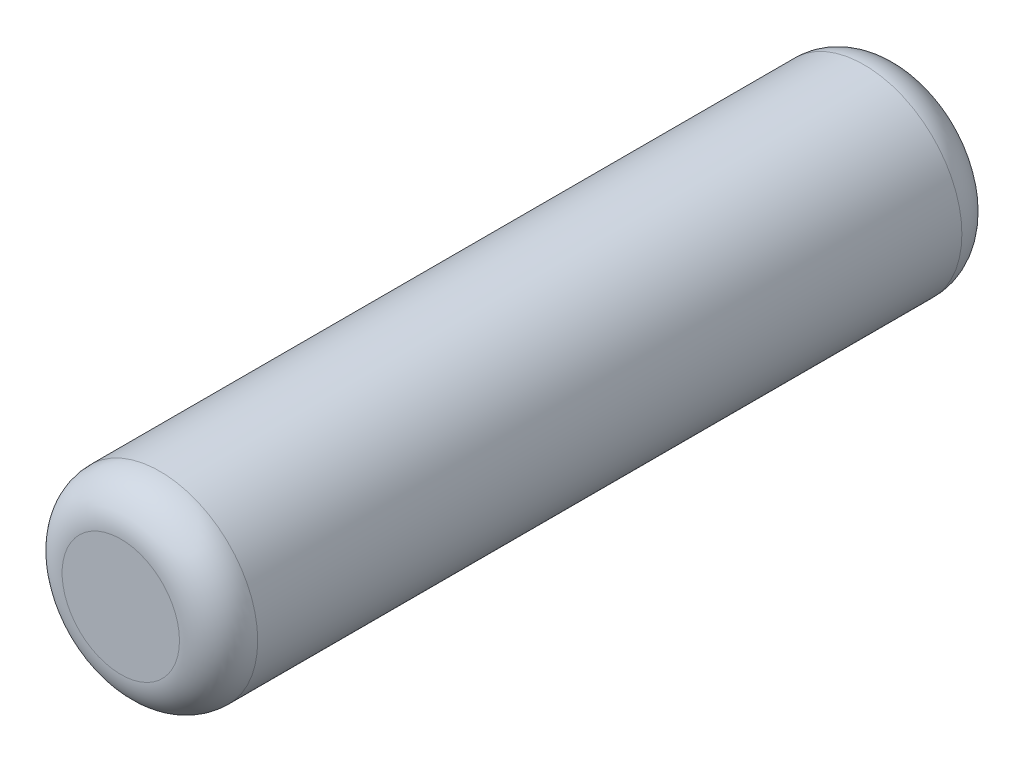
SolidWorks part; units mm, degrees
ref_plane "Front Plane" through (0, 0, 0) normal (0, 0, 1) x (1, 0, 0)
ref_plane "Top Plane" through (0, 0, 0) normal (0, 1, 0) x (1, 0, 0)
ref_plane "Right Plane" through (0, 0, 0) normal (1, 0, 0) x (0, 0, -1)
sketch "Sketch1" plane through (0, 0, 0) normal (0, 0, 1) x (1, 0, 0)
  circle A0 centre (0, 0) radius 2.5
  dimension "D1" = 5
extrude "Boss-Extrude1" add sketch "Sketch1" along normal blind 20
fillet "Fillet1" radius 1 2 edges at (2.5, 0, 0) (2.5, 0, 20)
